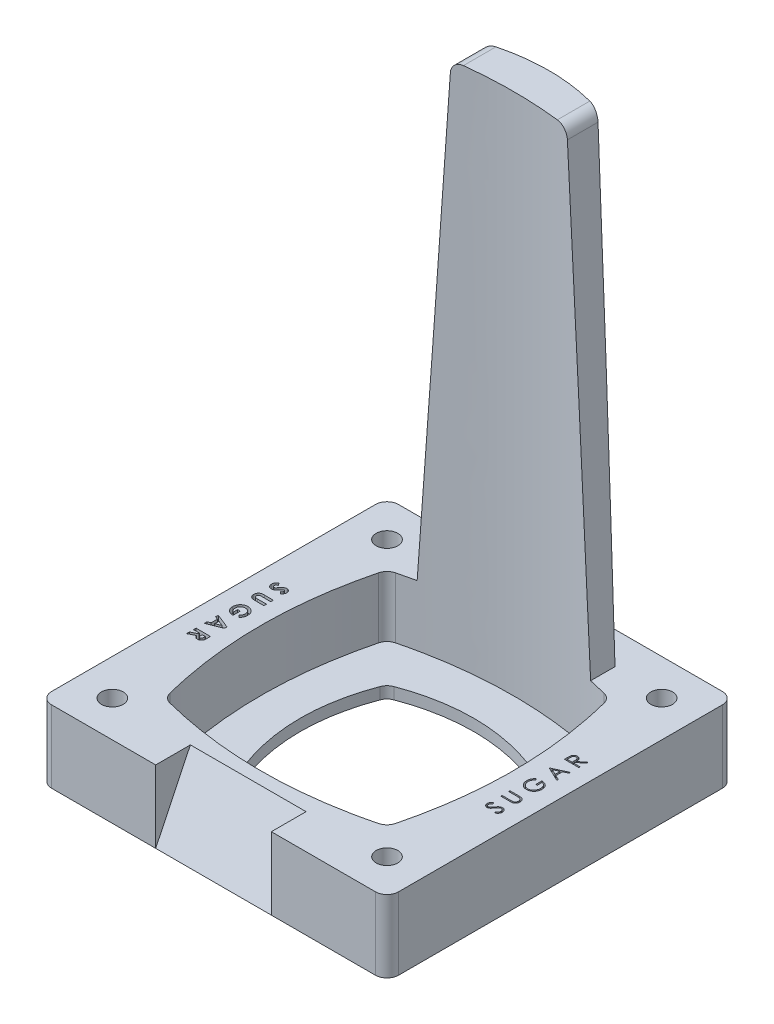
SolidWorks part; units mm, degrees
ref_plane "Front Plane" through (0, 0, 0) normal (0, 0, 1) x (1, 0, 0)
ref_plane "Top Plane" through (0, 0, 0) normal (0, 1, 0) x (1, 0, 0)
ref_plane "Right Plane" through (0, 0, 0) normal (1, 0, 0) x (0, 0, -1)
sketch "Sketch1" plane through (0, 0, 0) normal (0, 1, 0) x (1, 0, 0)
  line L1 (-38.1, -38.1) -> (38.1, -38.1)
  line L2 (-38.1, -38.1) -> (-38.1, 38.1)
  line L3 (-38.1, 38.1) -> (38.1, 38.1)
  line L4 (38.1, -38.1) -> (38.1, 38.1)
  line L5 (-38.1, -38.1) -> (38.1, 38.1) construction
  line L6 (-38.1, 38.1) -> (38.1, -38.1) construction
  point P0 (0, 0)
  dimension "D1" = 76.2
  dimension "D2" = 76.2
extrude "Boss-Extrude1" add sketch "Sketch1" along normal blind 15.875
sketch "Sketch2" plane through (0, 15.875, 0) normal (0, 1, 0) x (1, 0, 0)
  line L0 (-27.686, 0) -> (29.454, 0) construction
  line L1 (-24.384, -24.384) -> (24.384, -24.384) construction
  line L2 (-24.384, -24.384) -> (-24.384, 24.384) construction
  line L3 (-24.384, 24.384) -> (24.384, 24.384) construction
  line L4 (24.384, -24.384) -> (24.384, 24.384) construction
  line L5 (-24.384, -24.384) -> (24.384, 24.384) construction
  line L6 (-24.384, 24.384) -> (24.384, -24.384) construction
  line L7 (-27.686, -27.686) -> (27.686, -27.686) construction
  line L8 (-27.686, -27.686) -> (-27.686, 27.686) construction
  line L9 (-27.686, 27.686) -> (27.686, 27.686) construction
  line L10 (27.686, -27.686) -> (27.686, 27.686) construction
  line L11 (-27.686, -27.686) -> (27.686, 27.686) construction
  line L12 (-27.686, 27.686) -> (27.686, -27.686) construction
  line L13 (0, 27.686) -> (0, -27.686) construction
  spline S0 degree 2 poles (-24.384, 24.384) (-30.988, 0) (-24.384, -24.384) knots 0 0 0 1 1 1
  spline S1 degree 2 poles (-24.384, 24.384) (0, 30.988) (24.384, 24.384) knots 0 0 0 1 1 1
  spline S2 degree 2 poles (24.384, 24.384) (30.988, 0) (24.384, -24.384) knots 0 0 0 1 1 1
  spline S3 degree 2 poles (24.384, -24.384) (0, -30.988) (-24.384, -24.384) knots 0 0 0 1 1 1
  point P0 (0, 0)
  point P6 (0, 0)
  dimension "D1" = 48.768
  dimension "D2" = 48.768
  dimension "D3" = 55.372
  dimension "D4" = 55.372
extrude "Cut-Extrude1" cut sketch "Sketch2" against normal blind 13.335
sketch "Sketch4" plane through (0, 15.875, 0) normal (0, 1, 0) x (1, 0, 0)
  line L1 (-30.1625, -30.1625) -> (30.1625, -30.1625) construction
  line L2 (-30.1625, -30.1625) -> (-30.1625, 30.1625) construction
  line L3 (-30.1625, 30.1625) -> (30.1625, 30.1625) construction
  line L4 (30.1625, -30.1625) -> (30.1625, 30.1625) construction
  line L5 (-30.1625, -30.1625) -> (30.1625, 30.1625) construction
  line L6 (-30.1625, 30.1625) -> (30.1625, -30.1625) construction
  circle A0 centre (-30.1625, 30.1625) radius 2.3813
  circle A1 centre (30.1625, 30.1625) radius 2.3812
  circle A2 centre (30.1625, -30.1625) radius 2.3812
  circle A3 centre (-30.1625, -30.1625) radius 2.3813
  point P0 (0, 0)
  dimension "D3" = 4.7625
  dimension "D4" = 4.7625
  dimension "D5" = 4.7625
  dimension "D6" = 4.7625
  dimension "D1" = 60.325
  dimension "D2" = 60.325
extrude "Cut-Extrude3" cut sketch "Sketch4" against normal through all
fillet "Fillet2" radius 2.54 4 edges at (-38.1, 7.9375, 38.1) (38.1, 7.9375, 38.1) (38.1, 7.9375, -38.1) (-38.1, 7.9375, -38.1)
sketch "Sketch8" plane through (0, 2.54, 0) normal (0, 1, 0) x (1, 0, 0)
  line L0 (-19.05, 0) -> (29.3905, 0) construction
  line L1 (-15.875, -15.875) -> (15.875, -15.875) construction
  line L2 (-15.875, -15.875) -> (-15.875, 15.875) construction
  line L3 (-15.875, 15.875) -> (15.875, 15.875) construction
  line L4 (15.875, -15.875) -> (15.875, 15.875) construction
  line L5 (-15.875, -15.875) -> (15.875, 15.875) construction
  line L6 (-15.875, 15.875) -> (15.875, -15.875) construction
  line L7 (-19.05, -19.05) -> (19.05, -19.05) construction
  line L8 (-19.05, -19.05) -> (-19.05, 19.05) construction
  line L9 (-19.05, 19.05) -> (19.05, 19.05) construction
  line L10 (19.05, -19.05) -> (19.05, 19.05) construction
  line L11 (-19.05, -19.05) -> (19.05, 19.05) construction
  line L12 (-19.05, 19.05) -> (19.05, -19.05) construction
  line L13 (0, 19.05) -> (0, -19.05) construction
  spline S0 degree 2 poles (-15.875, 15.875) (-22.225, 0) (-15.875, -15.875) knots 0 0 0 1 1 1
  spline S1 degree 2 poles (-15.875, 15.875) (0, 22.225) (15.875, 15.875) knots 0 0 0 1 1 1
  spline S2 degree 2 poles (15.875, 15.875) (22.225, 0) (15.875, -15.875) knots 0 0 0 1 1 1
  spline S3 degree 2 poles (15.875, -15.875) (0, -22.225) (-15.875, -15.875) knots 0 0 0 1 1 1
  point P0 (0, 0)
  point P5 (0, 0)
  dimension "D1" = 38.1
  dimension "D2" = 31.75
  dimension "D3" = 31.75
  dimension "D4" = 38.1
  dimension "D5" = 0
  dimension "D6" = 0
extrude "Cut-Extrude4" cut sketch "Sketch8" against normal through all
fillet "Fillet3" radius 2.54 8 edges at (15.875, 1.27, -15.875) (15.875, 1.27, 15.875) (-15.875, 1.27, 15.875) (-15.875, 1.27, -15.875) (-24.384, 9.2075, -24.384) (-24.384, 9.2075, 24.384) (24.384, 9.2075, 24.384) (24.384, 9.2075, -24.384)
sketch "Sketch9" plane through (0, 15.875, 0) normal (0, 1, 0) x (1, 0, 0)
  line L0 (-26.67, 26.67) -> (-24.384, 24.384)
  line L1 (-27.686, -27.686) -> (27.686, -27.686) construction
  line L2 (-27.686, -27.686) -> (-27.686, 27.686) construction
  line L3 (-27.686, 27.686) -> (27.686, 27.686) construction
  line L4 (27.686, -27.686) -> (27.686, 27.686) construction
  line L5 (-27.686, -27.686) -> (27.686, 27.686) construction
  line L6 (-27.686, 27.686) -> (27.686, -27.686) construction
  line L7 (-24.384, -24.384) -> (24.384, -24.384) construction
  line L8 (-24.384, -24.384) -> (-24.384, 24.384) construction
  line L9 (-24.384, 24.384) -> (24.384, 24.384) construction
  line L10 (24.384, -24.384) -> (24.384, 24.384) construction
  line L11 (-24.384, -24.384) -> (24.384, 24.384) construction
  line L12 (-24.384, 24.384) -> (24.384, -24.384) construction
  line L13 (-30.48, -35.56) -> (30.48, -35.56) construction
  line L14 (-30.48, -35.56) -> (-30.48, 35.56) construction
  line L15 (-30.48, 35.56) -> (30.48, 35.56) construction
  line L16 (30.48, -35.56) -> (30.48, 35.56) construction
  line L17 (-30.48, -35.56) -> (30.48, 35.56) construction
  line L18 (-30.48, 35.56) -> (30.48, -35.56) construction
  line L19 (26.67, -26.67) -> (-26.67, -26.67) construction
  line L20 (26.67, -26.67) -> (26.67, 26.67) construction
  line L21 (26.67, 26.67) -> (-26.67, 26.67) construction
  line L22 (-26.67, -26.67) -> (-26.67, 26.67) construction
  line L23 (26.67, -26.67) -> (-26.67, 26.67) construction
  line L24 (26.67, 26.67) -> (-26.67, -26.67) construction
  line L25 (26.67, 26.67) -> (24.384, 24.384)
  spline S0 degree 2 poles (-24.384, 24.384) (0, 30.988) (24.384, 24.384) knots 0 0 0 1 1 1
  spline S1 degree 2 poles (-26.67, 26.67) (0, 44.45) (26.67, 26.67) knots 0 0 0 1 1 1
  point P0 (0, 0)
  point P6 (0, 0)
  point P12 (0, 0)
  point P17 (0, 0)
  dimension "D1" = 55.372
  dimension "D2" = 55.372
  dimension "D3" = 48.768
  dimension "D4" = 48.768
  dimension "D5" = 71.12
  dimension "D6" = 60.96
  dimension "D7" = 53.34
  dimension "D8" = 53.34
extrude "Boss-Extrude2" add sketch "Sketch9" along normal blind 101.6
sketch "Sketch10" plane through (0, 0, 0) normal (0, 0, 1) x (1, 0, 0)
  line L0 (0, 122.457) -> (0, 0) construction
  line L1 (-12.7, 117.475) -> (-19.05, 15.875)
  line L2 (24.384, 117.475) -> (-24.384, 117.475) construction
  line L3 (-35.56, 15.875) -> (35.56, 15.875) construction
  line L4 (12.7, 117.475) -> (19.05, 15.875)
  line L7 (-12.7, 117.475) -> (-26.67, 117.475)
  line L8 (-26.67, 117.475) -> (-26.67, 15.875)
  line L9 (-26.67, 15.875) -> (-19.05, 15.875)
  line L10 (12.7, 117.475) -> (26.67, 117.475)
  line L11 (26.67, 117.475) -> (26.67, 15.875)
  line L12 (26.67, 15.875) -> (19.05, 15.875)
  dimension "D1" = 12.7
  dimension "D2" = 19.05
extrude "Cut-Extrude5" cut sketch "Sketch10" against normal through all
fillet "Fillet4" radius 2.54 2 edges at (12.7, 117.475, -30.1672) (-12.7, 117.475, -30.1672)
sketch "Sketch11" plane through (0, 0, 0) normal (1, 0, 0) x (0, 0, -1)
  line L0 (-30.48, 15.875) -> (-38.1, 0)
  line L1 (35.56, 15.875) -> (-35.56, 15.875) construction
  line L2 (-38.1, 0) -> (-38.1, 15.875)
  line L3 (-38.1, 15.875) -> (-30.48, 15.875)
  dimension "D1" = 7.62
extrude "Cut-Extrude6" cut sketch "Sketch11" against normal mid plane 25.4
sketch "Sketch12" plane through (0, 15.875, 0) normal (0, 1, 0) x (1, 0, 0)
  line L0 (-34.29, 23.8125) -> (-34.29, -23.8125) construction
  line L1 (-38.1, 35.56) -> (-38.1, -35.56) construction
  line L2 (0, 7.4868) -> (0, -6.0106) construction
  line L3 (34.29, 23.8125) -> (34.29, -23.8125) construction
  circle A0 centre (-30.1625, 30.1625) radius 2.3813 construction
  circle A1 centre (-30.1625, -30.1625) radius 2.3813 construction
  text T0 "<b>SUGAR</b>" font "Century Gothic" height 3.175
  text T1 "SUGAR" font "Century Gothic" height 3.175
  dimension "D1" = 6.35
  dimension "D2" = 6.35
  dimension "D3" = 3.81
extrude "Cut-Extrude7" cut sketch "Sketch12" against normal blind 1.27
